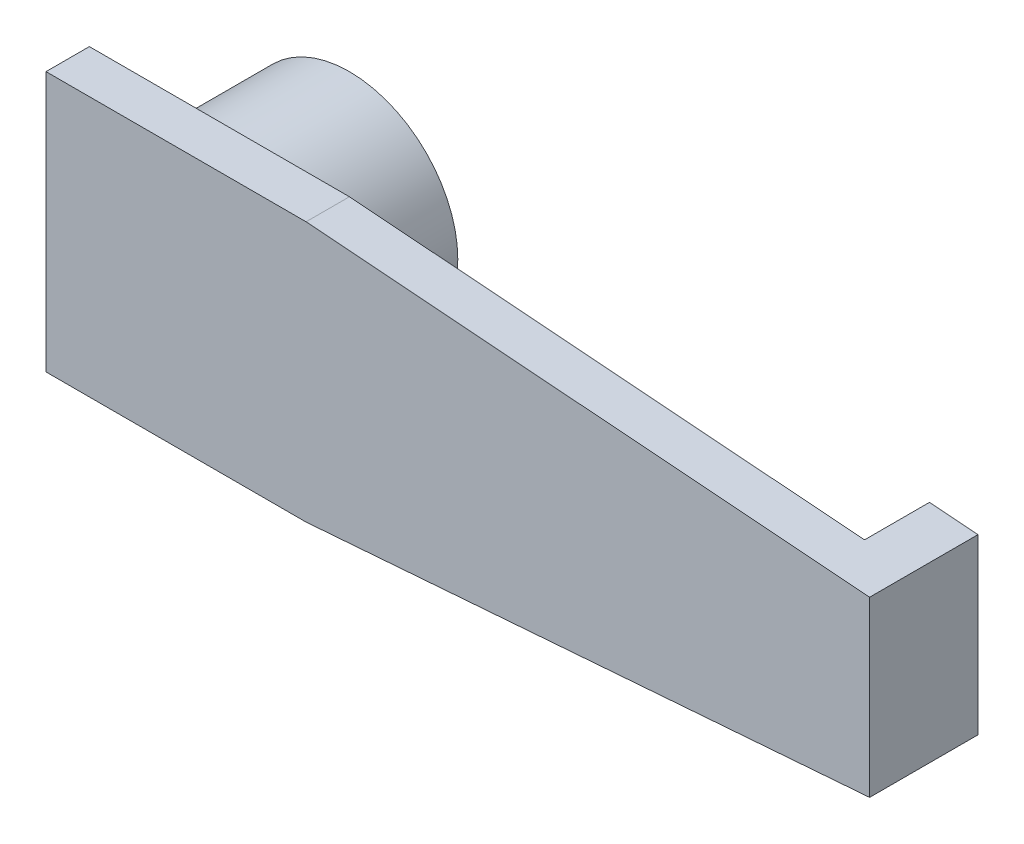
SolidWorks part; units mm, degrees
ref_plane "Front Plane" through (0, 0, 0) normal (0, 0, 1) x (1, 0, 0)
ref_plane "Top Plane" through (0, 0, 0) normal (0, 1, 0) x (1, 0, 0)
ref_plane "Right Plane" through (0, 0, 0) normal (1, 0, 0) x (0, 0, -1)
sketch "Sketch2" plane through (0, 0, 0) normal (0, 0, 1) x (1, 0, 0)
  circle A0 centre (0, 0) radius 12.5
  dimension "D1" = 25
extrude "Boss-Extrude1" add sketch "Sketch2" along normal blind 15 contours A0
sketch "Sketch3" plane through (0, 0, 15) normal (0, 0, 1) x (1, 0, 0)
  line L1 (-15, 15) -> (15, 15)
  line L2 (-15, 15) -> (-15, -15)
  line L3 (-15, -15) -> (15, -15)
  line L4 (15, 15) -> (15, -15)
  point P4 (-15, 0)
  point P7 (0, 15)
  dimension "D1" = 0
  dimension "D2" = 0
  dimension "D3" = 30
  dimension "D4" = 30
extrude "Boss-Extrude2" add sketch "Sketch3" along normal blind 5
ref_plane "Plane1" through (80, 0, 0) normal (1, 0, 0) x (0, 0, -1)
sketch "Sketch4" plane through (80, 0, 0) normal (1, 0, 0) x (0, 0, -1)
  line L0 (-20, -15) -> (-20, 15) construction
  line L1 (-20, 10) -> (-15, 10)
  line L2 (-20, 10) -> (-20, -10)
  line L3 (-20, -10) -> (-15, -10)
  line L4 (-15, 10) -> (-15, -10)
  line L5 (-15, -15) -> (-15, 15) construction
  point P8 (-15, 0)
  dimension "D1" = 20
  dimension "D2" = 0
sketch "Sketch5" plane through (15, 0, 0) normal (1, 0, 0) x (0, 0, -1)
  line L1 (-20, 15) -> (-15, 15)
  line L2 (-20, 15) -> (-20, -15)
  line L3 (-20, -15) -> (-15, -15)
  line L4 (-15, 15) -> (-15, -15)
loft "Loft1" add profiles "Sketch5", "Sketch4"
sketch "Sketch6" plane through (0, 0, 0) normal (0, 0, -1) x (-1, 0, 0)
  line L1 (-5, 5) -> (5, 5)
  line L2 (-5, 5) -> (-5, -5)
  line L3 (-5, -5) -> (5, -5)
  line L4 (5, 5) -> (5, -5)
  point P4 (0, 5)
  point P6 (-5, 0)
  dimension "D1" = 0
  dimension "D2" = 0
  dimension "D3" = 10
  dimension "D4" = 10
extrude "Cut-Extrude1" cut sketch "Sketch6" against normal blind 15
sketch "Sketch7" plane through (0, 0, 15) normal (0, 0, -1) x (-1, 0, 0)
  line L0 (-74.4075, 10.4302) -> (-74.4075, -10.4302)
  line L1 (-15, 15) -> (-80, 10) construction
  line L2 (-15, -15) -> (-80, -10) construction
  line L3 (-74.4075, -10.4302) -> (-80, -10)
  line L4 (-80, 11.0001) -> (-80, -11.0001) construction
  line L5 (-80, -10) -> (-80, 10)
  line L6 (-80, 10) -> (-74.4075, 10.4302)
extrude "Boss-Extrude3" add sketch "Sketch7" along normal blind 7.5
